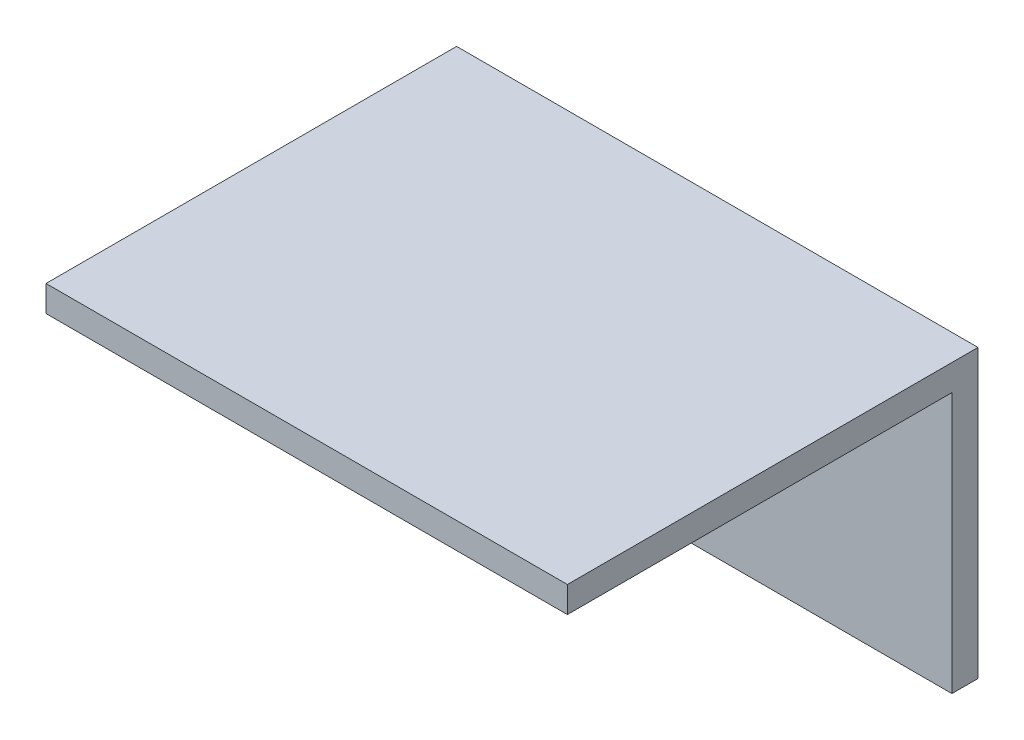
SolidWorks part; units mm, degrees
ref_plane "Front Plane" through (0, 0, 0) normal (0, 0, 1) x (1, 0, 0)
ref_plane "Top Plane" through (0, 0, 0) normal (0, 1, 0) x (1, 0, 0)
ref_plane "Right Plane" through (0, 0, 0) normal (1, 0, 0) x (0, 0, -1)
sketch "Sketch1" plane through (0, 0, 0) normal (0, 1, 0) x (1, 0, 0)
  line L0 (15.6259, 4.7746) -> (15.6259, 34.2746)
  line L1 (15.6259, 34.2746) -> (55.6259, 34.2746)
  line L2 (55.6259, 34.2746) -> (55.6259, 4.7746)
  line L3 (55.6259, 4.7746) -> (15.6259, 4.7746)
extrude "Boss-Extrude1" add sketch "Sketch1" along normal blind 2
sketch "Sketch2" plane through (0, 2, 0) normal (0, 1, 0) x (1, 0, 0)
  line L0 (55.6259, 34.2746) -> (55.6259, 36.2746)
  line L1 (55.6259, 36.2746) -> (15.6259, 36.2746)
  line L2 (15.6259, 36.2746) -> (15.6259, 34.2746)
  line L3 (15.6259, 34.2746) -> (55.6259, 34.2746)
extrude "Boss-Extrude2" add sketch "Sketch2" against normal blind 22
